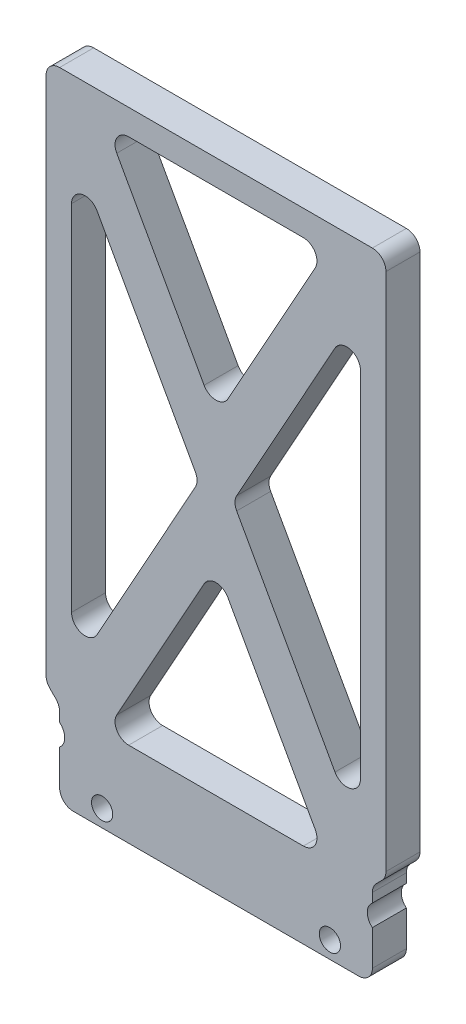
SolidWorks part; units mm, degrees
material "Aleación 1060"
ref_plane "Alzado" through (0, 0, 0) normal (0, 0, 1) x (1, 0, 0)
ref_plane "Planta" through (0, 0, 0) normal (0, 1, 0) x (1, 0, 0)
ref_plane "Vista lateral" through (0, 0, 0) normal (1, 0, 0) x (0, 0, -1)
sketch "Croquis1" plane through (0, 0, 0) normal (0, 0, 1) x (1, 0, 0)
  line L0 (-15, 24.3435) -> (25, 24.3435)
  line L1 (5, -18.4) -> (-15, -18.4) construction
  line L2 (-15, 24.3435) -> (-15, -50.6565)
  line L3 (5, -4) -> (5, -18.4) construction
  line L4 (25, 24.3435) -> (25, -50.6565)
  line L5 (-15, -50.6565) -> (25, -50.6565)
  line L6 (5, -50.6565) -> (5, -46.6565) construction
  line L7 (-13.4, -50.6565) -> (-13.4, -46.6565) construction
  circle A6 centre (-8.4, -48.6565) radius 1.25
  circle A7 centre (18.4, -48.6565) radius 1.25
  point P5 (5, -48.6565)
  dimension "D3" = 40
  dimension "D5" = 18.4
  dimension "D10" = 2.5
  dimension "D2" = 4
  dimension "D7" = 75
  dimension "D4" = 5
extrude "Saliente-Extruir1" add sketch "Croquis1" along normal blind 4
sketch "Croquis2" plane through (0, 0, 4) normal (0, 0, 1) x (1, 0, 0)
  line L0 (-15, 24.3435) -> (-15, -50.6565) construction
  line L1 (-12, -40.6565) -> (22, -40.6565) construction
  line L2 (-12, -40.6565) -> (-12, 21.3435) construction
  line L3 (-12, 21.3435) -> (22, 21.3435) construction
  line L4 (22, -40.6565) -> (22, 21.3435) construction
  line L5 (25, 24.3435) -> (-15, 24.3435) construction
  line L6 (-15, -50.6565) -> (25, -50.6565) construction
  line L7 (25, -50.6565) -> (25, 24.3435) construction
  line L8 (-12, -36.6565) -> (3, -9.6565)
  line L9 (-8, -40.6565) -> (5, -17.2565)
  line L10 (5, -40.6565) -> (5, -17.2565) construction
  line L11 (3, -9.6565) -> (-12, -9.6565) construction
  line L12 (-12, 17.3435) -> (3, -9.6565)
  line L13 (18, -40.6565) -> (5, -17.2565)
  line L14 (18, 21.3435) -> (5, -2.0565)
  line L15 (-8, 21.3435) -> (5, -2.0565)
  line L16 (22, 17.3435) -> (7, -9.6565)
  line L17 (22, -36.6565) -> (7, -9.6565)
  line L18 (-8, 21.3435) -> (18, 21.3435)
  line L19 (22, 17.3435) -> (22, -36.6565)
  line L20 (18, -40.6565) -> (-8, -40.6565)
  line L21 (-12, -36.6565) -> (-12, 17.3435)
  point P19 (-12, -9.6565)
  dimension "D1" = 3
  dimension "D2" = 3
  dimension "D3" = 10
  dimension "D4" = 3
  dimension "D5" = 4
  dimension "D6" = 4
  dimension "D7" = 2
extrude "Cortar-Extruir1" cut sketch "Croquis2" against normal up to vertex (4 mm away)
sketch "Croquis3" plane through (0, 0, 4) normal (0, 0, 1) x (1, 0, 0)
  line L0 (23.4, -50.6565) -> (-13.4, -50.6565) construction
  line L1 (-15, -50.6565) -> (25, -50.6565) construction
  line L2 (-15, 24.3435) -> (-15, -50.6565) construction
  line L3 (-13.4, -50.6565) -> (-15, -50.6565)
  line L4 (-13.4, -50.6565) -> (-13.4, -40.6565)
  line L5 (-13.4, -40.6565) -> (-15, -40.6565) construction
  line L6 (-15, -50.6565) -> (-15, -40.6565)
  line L7 (5, -50.6565) -> (5, -44.757) construction
  line L8 (25, -50.6565) -> (25, -40.6565)
  line L9 (23.4, -40.6565) -> (25, -40.6565) construction
  line L10 (23.4, -50.6565) -> (23.4, -40.6565)
  line L11 (23.4, -50.6565) -> (25, -50.6565)
  line L12 (-13.4, -40.6565) -> (-15, -39.0565)
  line L13 (-15, -39.0565) -> (-15, -40.6565)
  line L14 (23.4, -40.6565) -> (25, -39.0565)
  line L15 (25, -39.0565) -> (25, -40.6565)
  dimension "D1" = 18.4
  dimension "D2" = 10
extrude "Cortar-Extruir2" cut sketch "Croquis3" against normal up to vertex (4 mm away)
sketch "Croquis4" plane through (0, 0, 4) normal (0, 0, 1) x (1, 0, 0)
  line L0 (-13.4, -50.6565) -> (23.4, -50.6565) construction
  line L1 (-13.4, -50.6565) -> (-13.4, -40.6565) construction
  line L2 (5, -50.6565) -> (5, -40.6565) construction
  line L3 (-8, -40.6565) -> (18, -40.6565) construction
  circle A0 centre (-14.4, -43.6565) radius 1.6
  circle A1 centre (24.4, -43.6565) radius 1.6
  dimension "D1" = 7
  dimension "D3" = 3.2
  dimension "D2" = 1
extrude "Cortar-Extruir3" cut sketch "Croquis4" against normal up to vertex (4 mm away)
fillet "Redondeo2" radius 1.6 20 edges at (18, -40.6565, 2) (22, 17.3435, 2) (7, -9.6565, 2) (3, -9.6565, 2) (18, 21.3435, 2) (5, -17.2565, 2) (-12, -36.6565, 2) (-8, -40.6565, 2) (-12, 17.3435, 2) (-15, 24.3435, 2) (25, 24.3435, 2) (22, -36.6565, 2) (23.4, -50.6565, 2) (-13.4, -50.6565, 2) (-15, -39.0565, 2) (-13.4, -40.6565, 2) (23.4, -40.6565, 2) (25, -39.0565, 2) (5, -2.0565, 2) (-8, 21.3435, 2)
